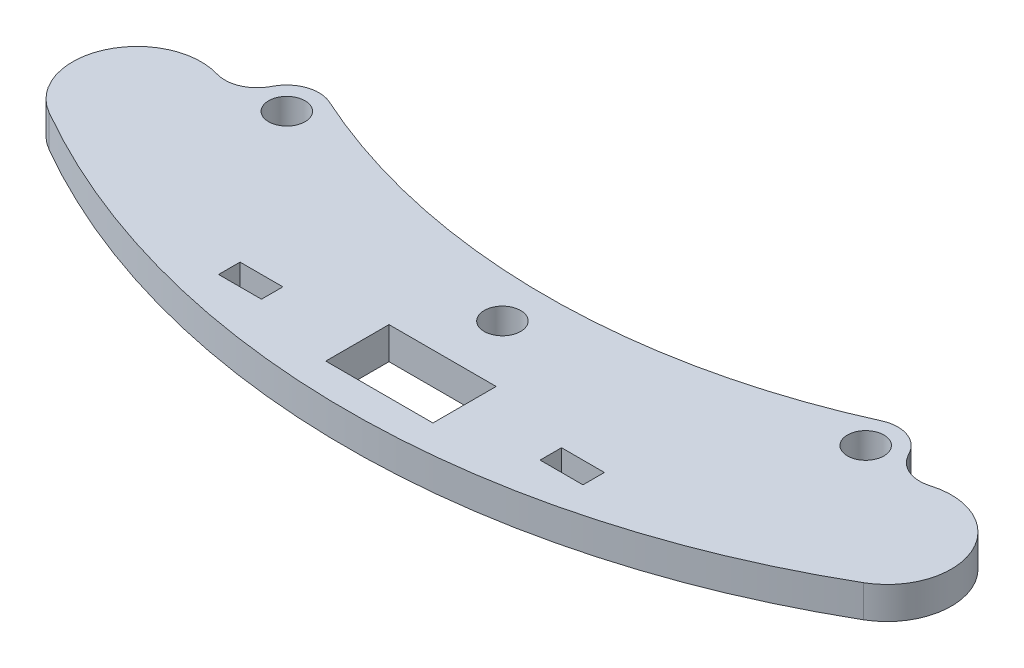
SolidWorks part; units mm, degrees
ref_plane "Alzado" through (0, 0, 0) normal (0, 0, 1) x (1, 0, 0)
ref_plane "Planta" through (0, 0, 0) normal (0, 1, 0) x (1, 0, 0)
ref_plane "Vista lateral" through (0, 0, 0) normal (1, 0, 0) x (0, 0, -1)
sketch "Croquis1" plane through (0, 0, 0) normal (0, 1, 0) x (1, 0, 0)
  line L2 (-29.6071, -53.1272) -> (-29.8221, -53.4995)
  line L3 (29.6071, -53.1272) -> (29.8221, -53.4995)
  arc A2 (-35, -60.6218) -> (35, -60.6218) centre (0, 0) ccw construction
  arc A3 (-38, -65.8179) -> (38, -65.8179) centre (0, 0) ccw
  arc A5 (-33.2801, -54.8736) -> (-38, -65.8179) centre (-35, -60.6218) ccw
  arc A6 (38, -65.8179) -> (33.2801, -54.8736) centre (35, -60.6218) ccw
  arc A7 (29.8221, -53.4995) -> (33.2801, -54.8736) centre (32.4201, -51.9995) ccw
  arc A8 (-29.8221, -53.4995) -> (-33.2801, -54.8736) centre (-32.4201, -51.9995) cw
  arc A10 (29.6071, -53.1272) -> (25.8239, -51.8712) centre (27.009, -54.6272) ccw
  arc A11 (-29.6071, -53.1272) -> (-25.8239, -51.8712) centre (-27.009, -54.6272) cw
  arc A13 (-25.8239, -51.8712) -> (25.8239, -51.8712) centre (0, 5.0085) ccw
  circle A14 centre (27.009, -54.6272) radius 1.7 construction
  circle A15 centre (0, -61.5151) radius 1.7 construction
  circle A16 centre (-27.009, -54.6272) radius 1.7 construction
  circle A17 centre (27.009, -54.6272) radius 1.7
  circle A18 centre (0, -61.5151) radius 1.7
  circle A19 centre (-27.009, -54.6272) radius 1.7
  point P1 (35, -60.6218)
  point P3 (-35, -60.6218)
  point P8 (0, -70)
  dimension "D4" = 6
  dimension "D5" = 6
  dimension "D6" = 6
extrude "Saliente-Extruir1" add sketch "Croquis1" along normal blind 3
sketch "Croquis2" plane through (0, 0, 0) normal (0, -1, 0) x (1, 0, 0)
  line L0 (0, 76) -> (0, 57.4589)
  arc A0 (38, 65.8179) -> (-38, 65.8179) centre (0, 0) ccw construction
  arc A1 (25.8239, 51.8712) -> (-25.8239, 51.8712) centre (0, -5.0085) ccw construction
  point P0 (35, 60.6218)
  point P1 (-35, 60.6218)
sketch "Croquis3" plane through (0, 0, 0) normal (0, -1, 0) x (1, 0, 0)
  line L0 (0, 57.4589) -> (0, 76) construction
  line L1 (13, 71) -> (13, 69)
  line L2 (-5, 73) -> (5, 73)
  line L3 (-5, 73) -> (-5, 67.1)
  line L4 (-5, 67.1) -> (5, 67.1)
  line L5 (5, 73) -> (5, 67.1)
  line L6 (-5, 73) -> (5, 67.1) construction
  line L7 (-5, 67.1) -> (5, 73) construction
  line L8 (-17, 71) -> (-13, 71)
  line L9 (-17, 71) -> (-17, 69)
  line L10 (-17, 69) -> (-13, 69)
  line L11 (-13, 71) -> (-13, 69)
  line L12 (-17, 71) -> (-13, 69) construction
  line L13 (-17, 69) -> (-13, 71) construction
  line L14 (17, 69) -> (13, 69)
  line L15 (17, 71) -> (17, 69)
  line L16 (17, 71) -> (13, 71)
  arc A0 (25.8239, 51.8712) -> (-25.8239, 51.8712) centre (0, -5.0085) ccw construction
  arc A1 (38, 65.8179) -> (-38, 65.8179) centre (0, 0) ccw construction
  point P8 (0, 70.05)
  point P13 (-15, 70)
  dimension "D1" = 5.9
  dimension "D2" = 10
  dimension "D3" = 3
  dimension "D4" = 15
  dimension "D5" = 4
  dimension "D6" = 2
  dimension "D7" = 6
extrude "Cortar-Extruir1" cut sketch "Croquis3" against normal up to next
